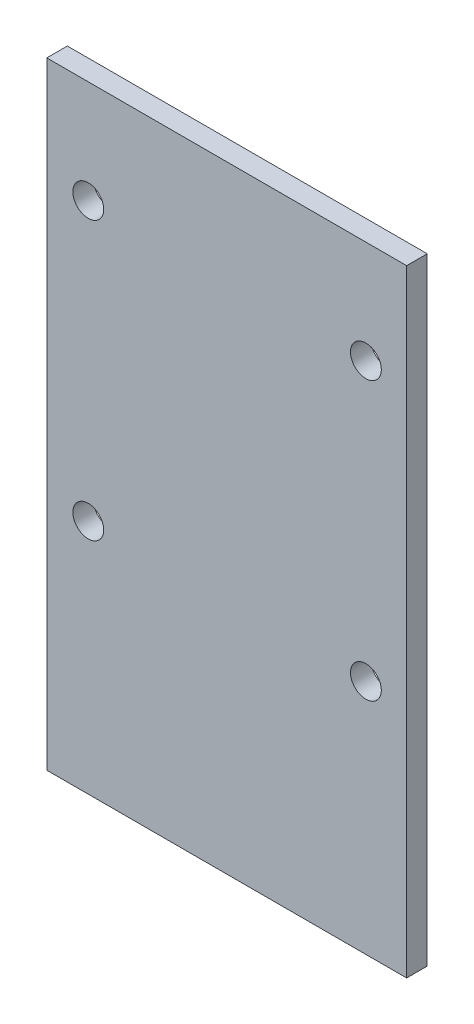
SolidWorks part; units mm, degrees
ref_plane "Front Plane" through (0, 0, 0) normal (0, 0, 1) x (1, 0, 0)
ref_plane "Top Plane" through (0, 0, 0) normal (0, 1, 0) x (1, 0, 0)
ref_plane "Right Plane" through (0, 0, 0) normal (1, 0, 0) x (0, 0, -1)
sketch "Sketch1" plane through (0, 0, 0) normal (0, 0, 1) x (1, 0, 0)
  line L1 (17.5, -30) -> (-17.5, -30)
  line L2 (17.5, -30) -> (17.5, 30)
  line L3 (17.5, 30) -> (-17.5, 30)
  line L4 (-17.5, -30) -> (-17.5, 30)
  line L5 (17.5, -30) -> (-17.5, 30) construction
  line L6 (17.5, 30) -> (-17.5, -30) construction
  point P0 (0, 0)
  dimension "D1" = 60
  dimension "D2" = 35
extrude "Boss-Extrude1" add sketch "Sketch1" along normal blind 2
sketch "Sketch2" plane through (0, 0, 2) normal (0, 0, 1) x (1, 0, 0)
  line L0 (17.5, 30) -> (-17.5, 30) construction
  circle A0 centre (-13.4643, 20) radius 1.5
  circle A1 centre (13.5357, 20) radius 1.5
  circle A2 centre (-13.4643, -7) radius 1.5
  circle A3 centre (13.5357, -7) radius 1.5
  dimension "D1" = 3
  dimension "D2" = 3
  dimension "D3" = 3
  dimension "D4" = 3
  dimension "D5" = 27
  dimension "D6" = 27
  dimension "D7" = 27
  dimension "D8" = 27
  dimension "D9" = 10
  dimension "D10" = 13.4643
  dimension "D11" = 13.5357
extrude "Cut-Extrude1" cut sketch "Sketch2" against normal blind 2
